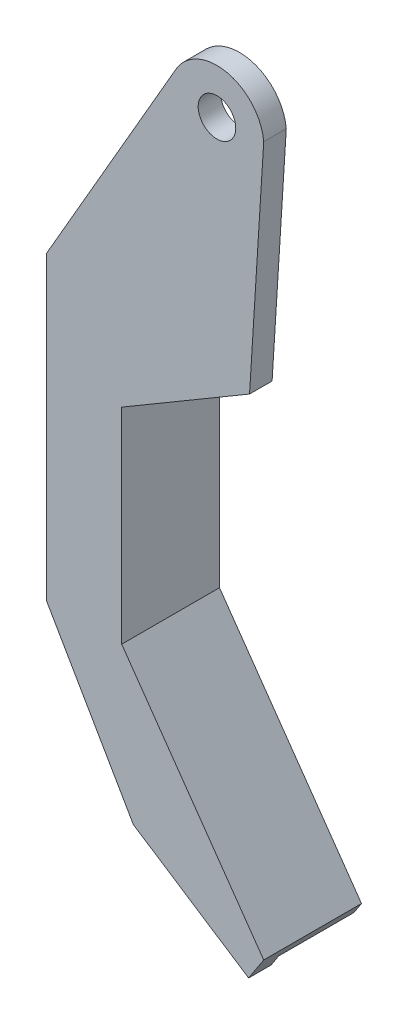
SolidWorks part; units mm, degrees
ref_plane "前视基准面" through (0, 0, 0) normal (0, 0, 1) x (1, 0, 0)
ref_plane "上视基准面" through (0, 0, 0) normal (0, 1, 0) x (1, 0, 0)
ref_plane "右视基准面" through (0, 0, 0) normal (1, 0, 0) x (0, 0, -1)
sketch "草图1" plane through (0, 0, 0) normal (0, 0, 1) x (1, 0, 0)
  line L0 (0.4413, 66.8945) -> (-16.8792, 36.8945)
  line L1 (-16.8792, 36.8945) -> (-16.8792, -3.1055)
  line L2 (-16.8792, -3.1055) -> (-5.3322, -23.1055)
  line L5 (-7.0008, 37.5151) -> (-6.8792, 37.579)
  line L26 (-5.3322, -23.1055) -> (9.9927, -33.1055)
  line L27 (11.9998, 64.1907) -> (10.1143, 34.1907)
  line L28 (10.1143, 34.1907) -> (-6.8792, 24.1907)
  line L29 (-6.8792, 24.1907) -> (-6.8792, 14.1907)
  line L32 (-6.8792, 14.1907) -> (-6.8792, -3.1055)
  line L35 (-6.8792, -3.1055) -> (11.9998, -30.0298)
  line L36 (11.9998, -30.0298) -> (9.9927, -33.1055)
  arc A4 (0.4413, 66.8945) -> (11.9998, 64.1907) centre (5.7669, 63.6033) cw
  dimension "D7" = 30
  dimension "D8" = 10
  dimension "D9" = 10
  dimension "D6" = 10
  dimension "D1" = 150
  dimension "D2" = 150
  dimension "D3" = 30
  dimension "D4" = 40
  dimension "D5" = 20
  dimension "D10" = 10
sketch "草图2" plane through (0, 0, 0) normal (0, 0, 1) x (1, 0, 0)
  circle A2 centre (5.7844, 63.8812) radius 2.5
  dimension "D1" = 5
extrude "凸台-拉伸4" add sketch "草图1" along normal blind 3
extrude "切除-拉伸1" cut sketch "草图2" along normal through all
sketch "草图6" plane through (0, 0, 0) normal (0, 0, -1) x (-1, 0, 0)
  line L0 (6.8792, 24.1907) -> (8.2484, 24.1907)
  line L1 (8.2484, 24.1907) -> (8.2484, -3.1455)
  line L2 (8.2484, -3.1455) -> (-10.9962, -31.5677)
  line L3 (-11.9998, -30.0298) -> (-9.9927, -33.1055) construction
  line L13 (-11.9998, 64.1907) -> (-10.1143, 34.1907)
  line L14 (-10.1143, 34.1907) -> (6.8792, 24.1907)
  line L15 (6.8792, 24.1907) -> (6.8792, -3.1055)
  line L16 (6.8792, -3.1055) -> (-11.9998, -30.0298)
  line L17 (-11.9998, -30.0298) -> (-9.9927, -33.1055)
  line L18 (-9.9927, -33.1055) -> (5.3322, -23.1055)
  line L19 (5.3322, -23.1055) -> (16.8792, -3.1055)
  line L20 (16.8792, -3.1055) -> (16.8792, 36.8945)
  line L21 (16.8792, 36.8945) -> (-0.4413, 66.8945)
  line L24 (6.8792, 24.1907) -> (6.8792, -3.1055)
  line L25 (6.8792, -3.1055) -> (-11.9998, -30.0298)
  line L26 (-11.9998, -30.0298) -> (-10.9962, -31.5677)
  arc A1 (-0.4413, 66.8945) -> (-11.9998, 64.1907) centre (-5.7669, 63.6033) ccw
  dimension "D1" = 0
extrude "凸台-拉伸6" add sketch "草图6" along normal blind 10
